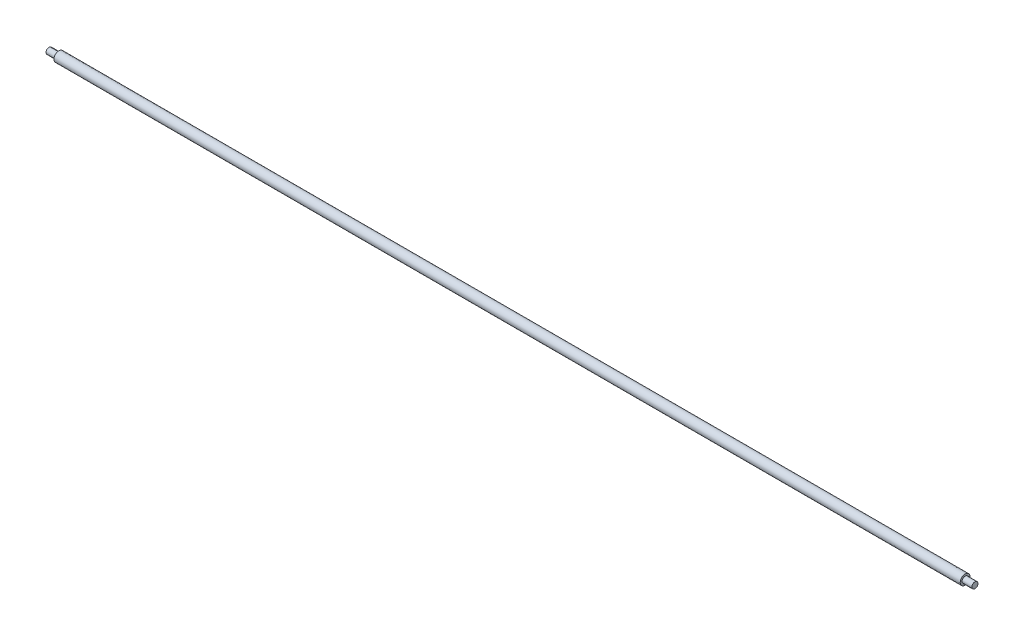
SolidWorks part; units mm, degrees
ref_plane "Front Plane" through (0, 0, 0) normal (0, 0, 1) x (1, 0, 0)
ref_plane "Top Plane" through (0, 0, 0) normal (0, 1, 0) x (1, 0, 0)
ref_plane "Right Plane" through (0, 0, 0) normal (1, 0, 0) x (0, 0, -1)
sketch "Sketch1" plane through (0, 0, 0) normal (1, 0, 0) x (0, 0, -1)
  circle A0 centre (0, 0) radius 1.651 construction
  circle A2 centre (0, 0) radius 1.0262 construction
  dimension "Wire Diameter" = 2.0523
  dimension "OD" = 3.302
sketch "Sketch2" plane through (0, 0, 0) normal (0, 0, 1) x (1, 0, 0)
  line L0 (-152.4, 0) -> (152.4, 0) construction
  line L1 (152.4, 0) -> (159.004, 0) construction
  line L2 (159.004, 0) -> (155.702, 0) construction
  line L4 (0, -1.651) -> (0, 1.651) construction
  line L5 (-152.4, 1.651) -> (-152.4, -1.651) construction
  line L6 (152.4, 1.651) -> (152.4, -1.651) construction
  line L7 (-152.4, 0) -> (-155.702, 0) construction
  line L8 (-155.702, 1.0262) -> (-155.702, -1.0262) construction
  line L9 (0, -1.0262) -> (0, 1.0262) construction
  line L10 (0, -1.0262) -> (0, 1.0262) construction
  line L11 (0, -1.651) -> (0, 1.651) construction
  point P3 (-147.447, 0)
  point P5 (147.447, 0)
  dimension "Length" = 304.8
  dimension "X" = 6.604
  dimension "Layer Length" = 3.302
  dimension "D3" = 3.302
  dimension "D2" = 4.953
  dimension "D1" = 4.953
sketch "Sketch3" plane through (0, 0, 0) normal (1, 0, 0) x (0, 0, -1)
  circle A0 centre (0, 0) radius 1.651 construction
  circle A1 centre (0, 0) radius 1.651
  circle A4 centre (0, 0) radius 1.0262 construction
  circle A6 centre (0, 0) radius 1.0262
extrude "Boss-Extrude1" add sketch "Sketch3" against normal mid plane 304.8
sketch "Sketch4" plane through (0, 0, 0) normal (1, 0, 0) x (0, 0, -1)
  circle A0 centre (0, 0) radius 1.0262 construction
  circle A1 centre (0, 0) radius 1.0262
extrude "Boss-Extrude2" add sketch "Sketch4" along normal up to vertex (155.702 mm away) and the other way up to vertex (155.702 mm away) separate body up to point (155.702, 0, 0) other way up to point (-155.702, 0, 0)
sketch "Sketch5" plane through (152.4, 0, 0) normal (1, 0, 0) x (0, 0, -1)
  circle A2 centre (0, 0) radius 1.0312
  circle A3 centre (0, 0) radius 1.0262 construction
  circle A4 centre (0, 0) radius 1.0262
  dimension "D1" = 0.0051
extrude "Cut-Extrude1" cut sketch "Sketch5" against normal through all
sketch "Reference Sketch1" plane through (0, 0, 0) normal (0, 1, 0) x (1, 0, 0)
  line L0 (152.4, 1.651) -> (152.4, -1.651) construction
  line L1 (-152.4, 1.651) -> (-152.4, -1.651) construction
  line L3 (155.702, -1.0262) -> (155.702, 1.0262) construction
  line L5 (0, -1.651) -> (0, 1.651) construction
  line L6 (0, -1.651) -> (0, 1.651) construction
  line L7 (0, -1.0262) -> (0, 1.0262) construction
  line L8 (0, -1.0262) -> (0, 1.0262) construction
  point P10 (155.702, 0)
equation "\"Layer Count\"= 2"
equation "\"X@Sketch2\" = \"OD@Sketch1\" * 2"
equation "\"Layer Length@Sketch2\" = \"X@Sketch2\" / \"Layer Count\""
equation "\"D3@Sketch2\"=\"X@Sketch2\"-\"Layer Length@Sketch2\""
equation "\"D1\"= \"Layer Length@Sketch2\""
equation "\"D2\"= \"Layer Length@Sketch2\""
equation "\"D1@Boss-Extrude1\"=\"Length@Sketch2\""
equation "\"D2@Sketch2\"=\"OD@Sketch1\" * 1.5"
equation "\"D1@Sketch2\"=\"OD@Sketch1\" * 1.5"
